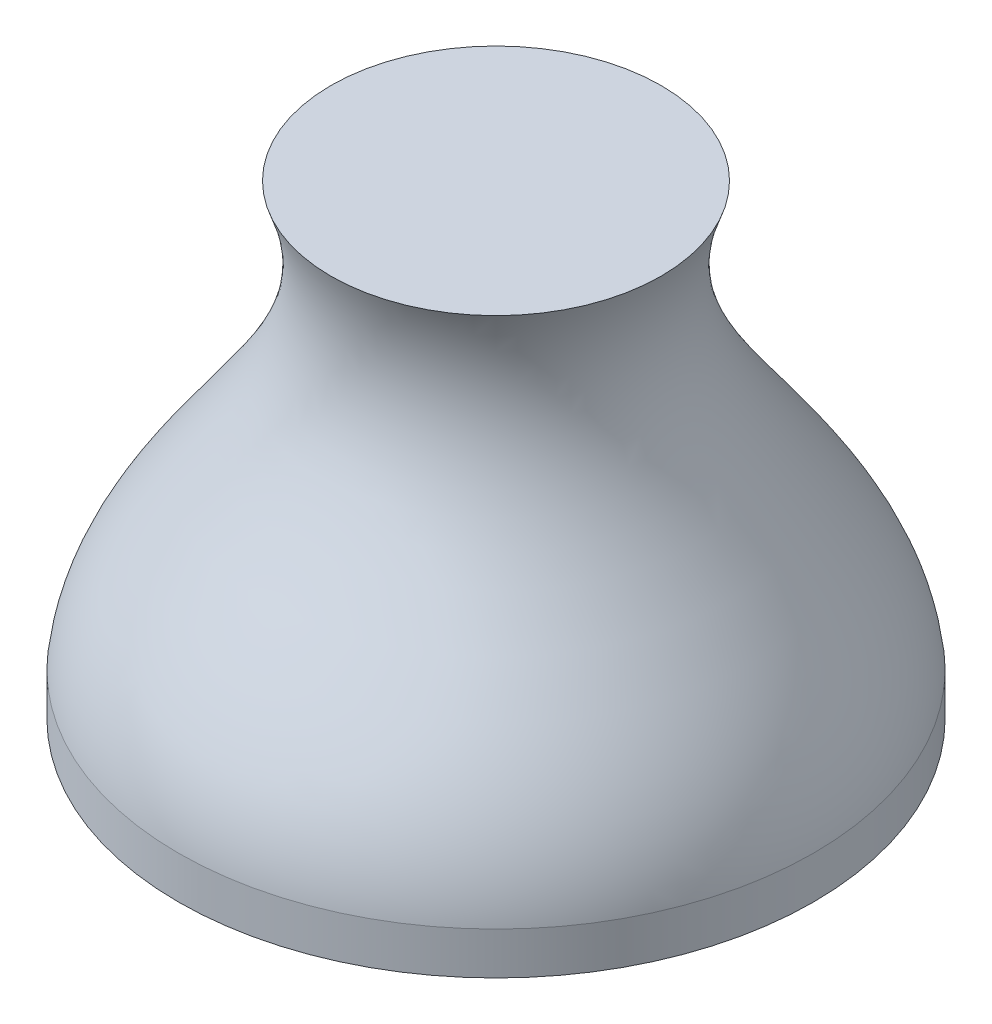
SolidWorks part; units mm, degrees
ref_plane "Front Plane" through (0, 0, 0) normal (0, 0, 1) x (1, 0, 0)
ref_plane "Top Plane" through (0, 0, 0) normal (0, 1, 0) x (1, 0, 0)
ref_plane "Right Plane" through (0, 0, 0) normal (1, 0, 0) x (0, 0, -1)
sketch "Sketch1" plane through (0, 0, 0) normal (0, 0, 1) x (1, 0, 0)
  line L0 (0, 0) -> (0, 20)
  line L1 (0, 20) -> (7.7995, 20)
  line L2 (0, 0) -> (15, 0)
  spline S0 degree 3 poles (7.7995, 20) (4.5026, 11.6925) (14.1433, 7.4203) (15, 0) knots 0 0 0 0 1 1 1 1
  point P4 (6.5744, 19.828)
  point P7 (0, 0)
  point P8 (0, 0)
  point P9 (7.7995, 20)
  point P10 (7.745, 13.403)
  point P11 (10.1952, 8.2576)
  point P12 (14.415, 2.3772)
revolve "Revolve1" add sketch "Sketch1" angle 360 about L0
sketch "Sketch2" plane through (0, 0, 0) normal (0, -1, 0) x (1, 0, 0)
  circle A0 centre (0, 0) radius 15
extrude "Boss-Extrude1" add sketch "Sketch2" along normal blind 2
